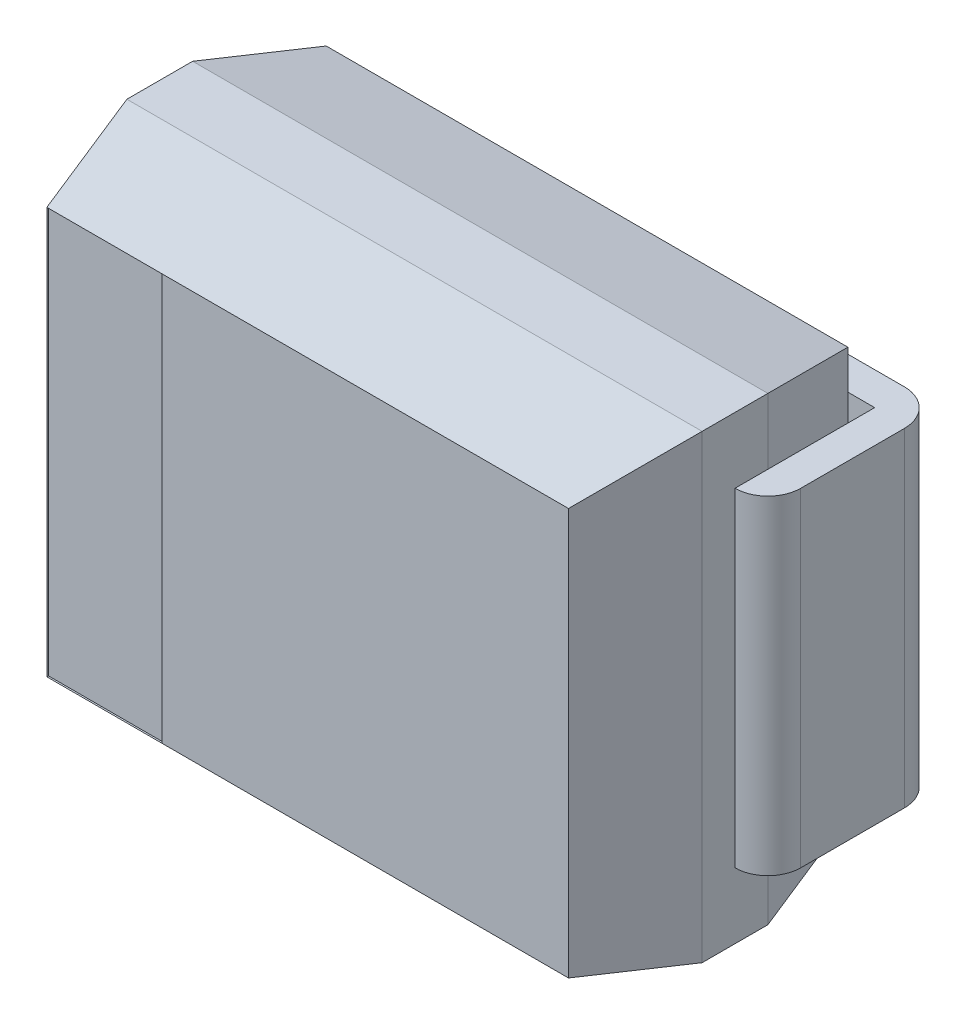
SolidWorks part; units mm, degrees
other "Детальный элемент1"
ref_plane "Спереди" through (0, 0, 0) normal (0, 0, 1) x (1, 0, 0)
ref_plane "Сверху" through (0, 0, 0) normal (0, 1, 0) x (1, 0, 0)
ref_plane "Справа" through (0, 0, 0) normal (1, 0, 0) x (0, 0, -1)
ref_plane "Плоскость1" through (0, 0, 0.2) normal (0, 0, 1) x (1, 0, 0)
sketch "Эскиз1" plane through (0, 0, 0.2) normal (0, 0, 1) x (1, 0, 0)
  line L1 (-1.75, 1.4) -> (1.75, 1.4)
  line L2 (-1.75, 1.4) -> (-1.75, -1.4)
  line L3 (-1.75, -1.4) -> (1.75, -1.4)
  line L4 (1.75, 1.4) -> (1.75, -1.4)
  line L5 (-1.75, 1.4) -> (1.75, -1.4) construction
  line L6 (-1.75, -1.4) -> (1.75, 1.4) construction
  point P0 (0, 0)
  dimension "D1" = 3.5
  dimension "D2" = 2.8
extrude "Бобышка-Вытянуть1" add sketch "Эскиз1" along normal blind 1.7
chamfer "Фаска1" distance 0.65 distance2 0.163 4 edges at (0, 1.4, 1.9) (1.75, 0, 1.9) (0, -1.4, 1.9) (-1.75, 0, 1.9)
chamfer "Фаска2" distance 0.163 distance2 0.65 4 edges at (1.75, 0, 0.2) (0, 1.4, 0.2) (0, -1.4, 0.2) (-1.75, 0, 0.2)
sketch "Эскиз2" plane through (0, 0, 0) normal (0, 1, 0) x (1, 0, 0)
  line L0 (-1.75, -0.2) -> (-1.75, -0.85)
  line L1 (-0.815, 0) -> (-1.73, 0)
  line L2 (-0.815, 0) -> (-0.815, -0.2)
  line L3 (-0.815, -0.2) -> (-1.75, -0.2)
  line L4 (-1.75, -0.85) -> (-1.75, -1.05)
  line L5 (-1.95, -0.85) -> (-1.95, -0.22)
  arc A2 (-1.75, -1.05) -> (-1.95, -0.85) centre (-1.75, -0.85) cw
  arc A3 (-1.73, 0) -> (-1.95, -0.22) centre (-1.73, -0.22) ccw
  dimension "D3" = 0.22
  dimension "D1" = 0.2
  dimension "D2" = 0.2
  dimension "D4" = 0.915
extrude "Бобышка-Вытянуть2" add sketch "Эскиз2" along normal blind 1 and the other way blind 1 separate body
mirror "Зеркальное отражение1" about plane through (0, 0, 0) normal (1, 0, 0) of bodies 108
sketch "Эскиз3" plane through (0, 0, 1.9) normal (0, 0, 1) x (1, 0, 0)
  line L0 (1.587, 1.237) -> (-1.587, 1.237) construction
  line L1 (-1.587, -1.237) -> (-0.887, -1.237)
  line L2 (-1.587, -1.237) -> (-1.587, 1.237)
  line L3 (-1.587, 1.237) -> (-0.887, 1.237)
  line L4 (-0.887, -1.237) -> (-0.887, 1.237)
  dimension "D1" = 0.7
extrude "Вырез-Вытянуть1" cut sketch "Эскиз3" against normal blind 0.01
